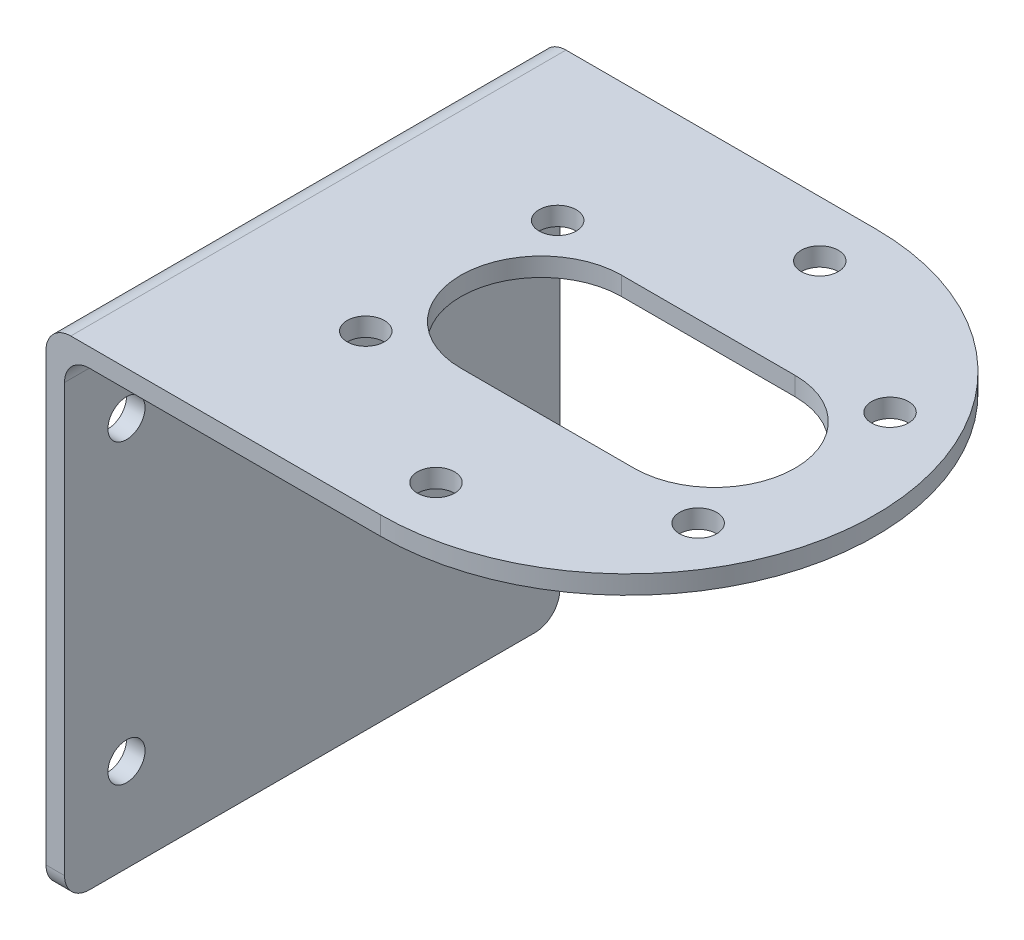
SolidWorks part; units mm, degrees
material "普通碳钢"
ref_plane "前视" through (0, 0, 0) normal (0, 0, 1) x (1, 0, 0)
ref_plane "上视" through (0, 0, 0) normal (0, 1, 0) x (1, 0, 0)
ref_plane "右视" through (0, 0, 0) normal (1, 0, 0) x (0, 0, -1)
sketch "草图1" plane through (0, 0, 0) normal (0, 0, 1) x (1, 0, 0)
  line L0 (0, -40) -> (0, -2)
  line L1 (2, 0) -> (50, 0)
  line L2 (1.5, -40) -> (1.5, -3.5)
  line L3 (3.5, -1.5) -> (50, -1.5)
  line L4 (0, -40) -> (1.5, -40)
  line L5 (50, 0) -> (50, -1.5)
  line L6 (1.5, -40) -> (1.5, -1.5) construction
  line L7 (1.5, -1.5) -> (50, -1.5) construction
  line L8 (0, -40) -> (0, 0) construction
  line L9 (0, 0) -> (50, 0) construction
  arc A0 (1.5, -3.5) -> (3.5, -1.5) centre (3.5, -3.5) cw
  arc A1 (0, -2) -> (2, 0) centre (2, -2) cw
  point P13 (0, 0)
  dimension "D4" = 2
  dimension "D2" = 40
  dimension "D3" = 50
  dimension "D1" = 1.5
extrude "凸台-拉伸1" add sketch "草图1" along normal mid plane 40 contours L3 L5 L1 A1 L0 L4 L2 A0
sketch "草图3" plane through (0, -1.5, 0) normal (0, -1, 0) x (1, 0, 0)
  line L0 (27, 20) -> (27, -20) construction
  line L1 (3.5, 20) -> (50, 20) construction
  line L2 (3.5, -20) -> (50, -20) construction
  line L3 (27, 20) -> (50, 20)
  line L4 (27, -20) -> (50, -20)
  line L5 (0, 0) -> (47, 0) construction
  line L6 (50, -20) -> (50, 20)
  line L7 (34, 0) -> (20, 0) construction
  line L8 (34, -6.5) -> (20, -6.5)
  line L9 (34, 6.5) -> (20, 6.5)
  line L10 (50, 0) -> (0, 0) construction
  arc A0 (27, 20) -> (27, -20) centre (27, 0) cw
  arc A1 (34, -6.5) -> (34, 6.5) centre (34, 0) ccw
  arc A2 (20, 6.5) -> (20, -6.5) centre (20, 0) ccw
  point P13 (27, 0)
  dimension "D2" = 27
  dimension "D1" = 47
  dimension "D3" = 13
extrude "切除-拉伸2" cut sketch "草图3" against normal blind 40
sketch "草图4" plane through (0, -1.5, 0) normal (0, -1, 0) x (1, 0, 0)
  line L0 (27, 20) -> (27, -20) construction
  line L1 (3.5, 20) -> (27, 20) construction
  line L2 (0, 0) -> (47, 0) construction
  arc A0 (27, -20) -> (27, 20) centre (27, 0) ccw construction
  circle A1 centre (27, -15.5) radius 1.5
  dimension "D1" = 3
  dimension "D2" = 31
extrude "切除-拉伸3" cut sketch "草图4" against normal blind 40
sketch "草图5" plane through (0, 0, 0) normal (-1, 0, 0) x (0, 0, 1)
  line L0 (0, 0) -> (0, -40) construction
  line L1 (20, -40) -> (-20, -40) construction
  line L3 (20, 0) -> (-20, 0) construction
  circle A0 centre (15, -8.5) radius 1.5
  circle A1 centre (15, -32.5) radius 1.5
  circle A2 centre (-15, -32.5) radius 1.5
  circle A3 centre (-15, -8.5) radius 1.5
  dimension "D1" = 3
  dimension "D2" = 24
  dimension "D3" = 30
  dimension "D4" = 8.5
  dimension "D5" = 30
extrude "切除-拉伸4" cut sketch "草图5" against normal blind 40
fillet "圆角1" radius 2 2 edges at (0.75, -40, -20) (0.75, -40, 20)
sketch "草图6" plane through (0, 0, 0) normal (0, 1, 0) x (1, 0, 0)
  line L0 (27, 15.5) -> (27, -6.5) construction
  line L1 (20, -6.5) -> (34, -6.5) construction
  line L2 (40.5, 0) -> (13.5, 0) construction
  arc A0 (34, -6.5) -> (34, 6.5) centre (34, 0) ccw construction
  arc A1 (20, 6.5) -> (20, -6.5) centre (20, 0) ccw construction
  circle A2 centre (27, 0) radius 5
  dimension "D1" = 10
pattern_circular "阵列(圆周)1" count 6 over 360 about axis through (27, 0, 0) along (0, 1, 0) of "切除-拉伸3"
